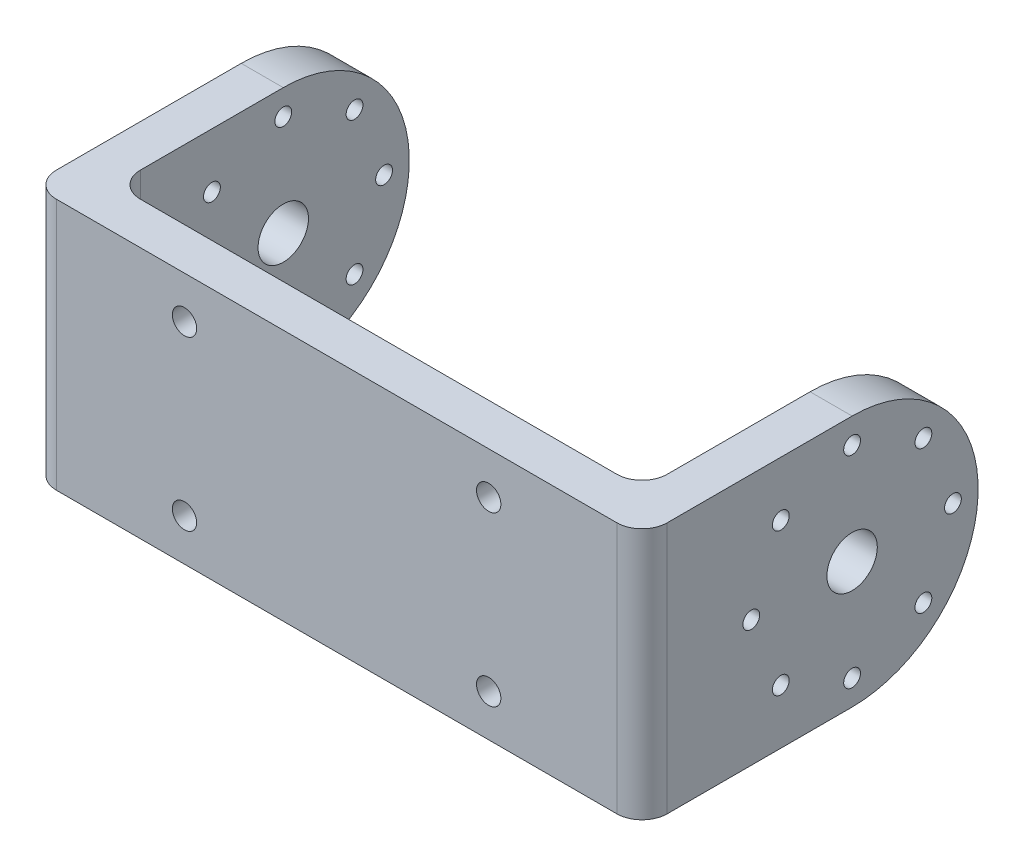
SolidWorks part; units mm, degrees
ref_plane "Front Plane" through (0, 0, 0) normal (0, 0, 1) x (1, 0, 0)
ref_plane "Top Plane" through (0, 0, 0) normal (0, 1, 0) x (1, 0, 0)
ref_plane "Right Plane" through (0, 0, 0) normal (1, 0, 0) x (0, 0, -1)
sketch "Sketch1" plane through (0, 0, 0) normal (0, 0, 1) x (1, 0, 0)
  line L0 (36.35, -15) -> (36.35, 15)
  line L1 (-36.35, -15) -> (-36.35, 15)
  line L2 (0, 0) -> (-36.35, 0)
  line L3 (0, 0) -> (36.35, 0)
  line L4 (-36.35, 15) -> (36.35, 15)
  line L5 (-36.35, -15) -> (36.35, -15)
  circle A0 centre (0, 0) radius 5
  point P10 (-36.35, 0)
  point P11 (36.35, 0)
  dimension "D1" = 10
  dimension "D2" = 30
  dimension "D4" = 36.35
  dimension "D5" = 36.35
extrude "Boss-Extrude1" add sketch "Sketch1" along normal blind 5 contours A0 L3 L0 L4 L1 L2 | L3 A0 L2 | L2 A0 L3 | A0 L2 L1 L5 L0 L3
sketch "Sketch4" plane through (0, 0, 0) normal (0, 0, -1) x (-1, 0, 0)
  line L0 (36.35, 15) -> (-36.35, 15) construction
  line L1 (-36.35, -15) -> (-31.35, -15)
  line L2 (-36.35, -15) -> (-36.35, 15)
  line L3 (-36.35, 15) -> (-31.35, 15)
  line L4 (-31.35, -15) -> (-31.35, 15)
  dimension "D1" = 5
extrude "Boss-Extrude4" add sketch "Sketch4" along normal blind 35
sketch "Sketch5" plane through (36.35, 0, 0) normal (1, 0, 0) x (0, 0, -1)
  line L0 (35, 0) -> (20, 0)
  line L1 (35, 15) -> (35, -15) construction
  circle A0 centre (20, 0) radius 15
  circle A1 centre (20, 0) radius 3
  dimension "D2" = 6
  dimension "D1" = 15
extrude "Cut-Extrude2" cut sketch "Sketch5" against normal blind 40
sketch "Sketch6" plane through (31.35, 0, 0) normal (-1, 0, 0) x (0, 0, 1)
  line L0 (-35, 15) -> (0, 15) construction
  line L1 (-35, -15) -> (0, -15) construction
  line L2 (-20, 15) -> (-35, 15)
  line L3 (-35, 15) -> (-35, -15)
  line L4 (-35, -15) -> (-20, -15)
  arc A0 (-20, 15) -> (-20, -15) centre (-20, 0) ccw
  circle A1 centre (-20, 0) radius 15 construction
  line M7 (0, 15) -> (-35, 15)
  line M8 (-35, 15) -> (-35, -15)
  line M9 (-35, -15) -> (0, -15)
extrude "Cut-Extrude3" cut sketch "Sketch6" against normal blind 10 contours A0 M7 M8 | A0 L3 M9
sketch "Sketch7" plane through (31.35, 0, 0) normal (-1, 0, 0) x (0, 0, 1)
  circle A0 centre (-28.4853, 8.4853) radius 1
  circle A1 centre (-11.5147, 8.4853) radius 1
  circle A2 centre (-8, 0) radius 1
  circle A3 centre (-32, 0) radius 1
  circle A4 centre (-11.5147, -8.4853) radius 1
  circle A6 centre (-20, 12) radius 1
  circle A7 centre (-28.4853, -8.4853) radius 1
  circle A8 centre (-20, -12) radius 1
extrude "Cut-Extrude4" cut sketch "Sketch7" against normal blind 10
fillet "Fillet2" radius 3 1 edges at (36.35, 0, 5)
fillet "Fillet3" radius 3 1 edges at (31.35, 0, 0)
mirror "Mirror2" about plane through (0, 0, 0) normal (1, 0, 0) of "Cut-Extrude3", "Cut-Extrude2", "Boss-Extrude4", "Cut-Extrude4"
fillet "Fillet5" radius 3 1 edges at (-36.35, 0, 5)
fillet "Fillet6" radius 3 1 edges at (-31.35, 0, 0)
sketch "Sketch8" plane through (0, 0, 5) normal (0, 0, 1) x (1, 0, 0)
  line L0 (-18.1, 10) -> (18.1, 10) construction
  line L1 (0, 10) -> (0, 15) construction
  line L2 (-18.1, 10) -> (-18.1, -10) construction
  line L3 (-18.1, -10) -> (18.1, -10) construction
  line L4 (18.1, -10) -> (18.1, 10) construction
  line L5 (-33.35, 15) -> (33.35, 15) construction
  line L7 (-33.35, -15) -> (33.35, -15) construction
  circle A0 centre (-18.1, 10) radius 1.45
  circle A1 centre (18.1, 10) radius 1.45
  circle A2 centre (18.1, -10) radius 1.45
  circle A3 centre (-18.1, -10) radius 1.45
  point P13 (0, 15)
  dimension "D1" = 5
  dimension "D2" = 5
extrude "Cut-Extrude6" cut sketch "Sketch8" against normal blind 4
equation "\"mm\"=35"
